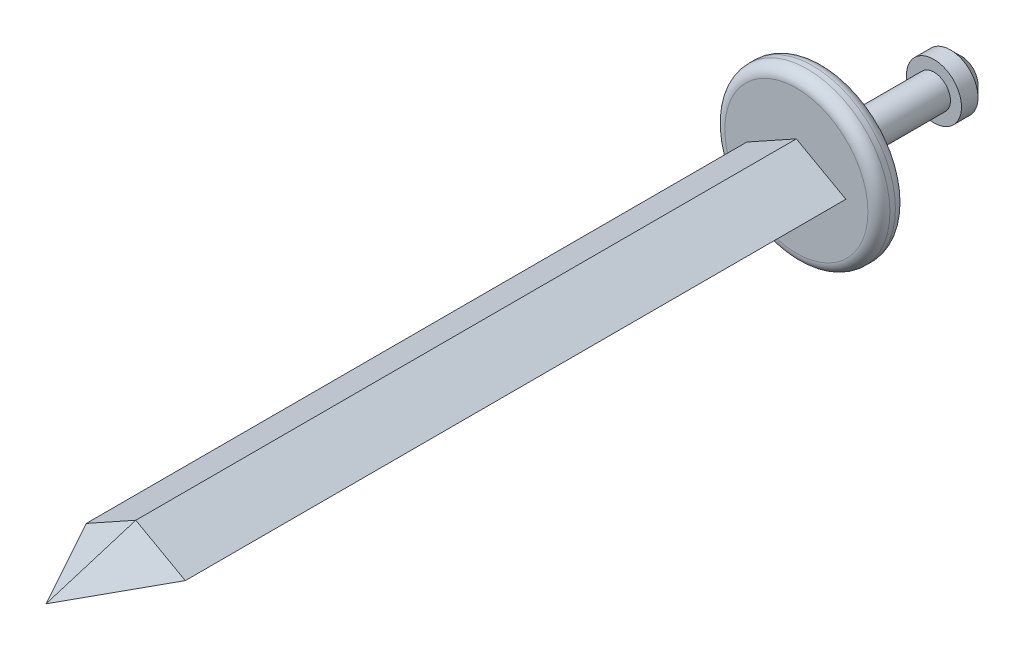
SolidWorks part; units mm, degrees
material "1.1191 (C45E)"
ref_plane "前视基准面" through (0, 0, 0) normal (0, 0, 1) x (1, 0, 0)
ref_plane "上视基准面" through (0, 0, 0) normal (0, 1, 0) x (1, 0, 0)
ref_plane "右视基准面" through (0, 0, 0) normal (1, 0, 0) x (0, 0, -1)
sketch "草图1" plane through (0, 0, 0) normal (0, 0, 1) x (1, 0, 0)
  circle A0 centre (0, 0) radius 15
  dimension "D1" = 30
extrude "凸台-拉伸1" add sketch "草图1" along normal blind 5
fillet "圆角1" radius 2 2 edges at (15, 0, 0) (15, 0, 5)
sketch "草图2" plane through (0, 0, 0) normal (0, 0, -1) x (-1, 0, 0)
  circle A0 centre (0, 0) radius 5
  dimension "D1" = 10
extrude "凸台-拉伸2" add sketch "草图2" along normal blind 25
chamfer "倒角2" distance 2 1 edges at (-5, 0, -25)
sketch "草图3" plane through (0, 0, 0) normal (0, 1, 0) x (1, 0, 0)
  line L0 (0, 0) -> (0, 23) construction
  line L9 (3, 0) -> (3, 20)
  line L11 (5, 20) -> (5, 0)
  line L12 (-5, 23) -> (5, 23) construction
  line L13 (3, 20) -> (5, 20)
  line L14 (3, 0) -> (5, 0)
  line L15 (-3, 0) -> (-5, 0)
  line L16 (-5, 20) -> (-5, 0)
  line L17 (-3, 20) -> (-5, 20)
  line L18 (-3, 0) -> (-3, 20)
  dimension "D1" = 3
  dimension "D3" = 2
revolve "切除-旋转2" cut sketch "草图3" angle 360 about L0
sketch "草图5" plane through (0, 0, 5) normal (0, 0, 1) x (1, 0, 0)
  line L0 (-9, 0) -> (0, -5)
  line L1 (-9, 0) -> (0, 5)
  line L2 (0, -5) -> (9, 0)
  line L3 (0, 5) -> (9, 0)
  line L4 (-9, 0) -> (9, 0) construction
  line L5 (0, 5) -> (0, -5) construction
  point P0 (0, 0)
  dimension "D1" = 18
  dimension "D2" = 10
extrude "凸台-拉伸4" add sketch "草图5" along normal blind 120
sketch "草图8" plane through (0, 0, 125) normal (0, 0, 1) x (1, 0, 0)
  line L0 (0, -5) -> (9, 0)
  line L1 (9, 0) -> (0, 5)
  line L2 (0, 5) -> (-9, 0)
  line L3 (-9, 0) -> (0, -5)
extrude "凸台-拉伸5" add sketch "草图8" along normal blind 20 draft 15
